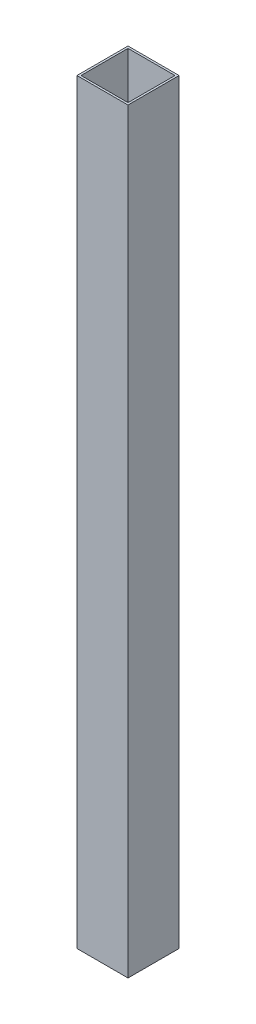
SolidWorks part; units mm, degrees
ref_plane "Front Plane" through (0, 0, 0) normal (0, 0, 1) x (1, 0, 0)
ref_plane "Top Plane" through (0, 0, 0) normal (0, 1, 0) x (1, 0, 0)
ref_plane "Right Plane" through (0, 0, 0) normal (1, 0, 0) x (0, 0, -1)
sketch "Sketch1" plane through (0, 0, 0) normal (0, 1, 0) x (1, 0, 0)
  line L1 (-25, 25) -> (25, 25)
  line L2 (-25, 25) -> (-25, -25)
  line L3 (-25, -25) -> (25, -25)
  line L4 (25, 25) -> (25, -25)
  line L5 (-25, 25) -> (25, -25) construction
  line L6 (-25, -25) -> (25, 25) construction
  point P0 (0, 0)
  dimension "D1" = 50
  dimension "D2" = 50
extrude "Boss-Extrude1" add sketch "Sketch1" along normal blind 740
shell "Shell1" thickness 2
